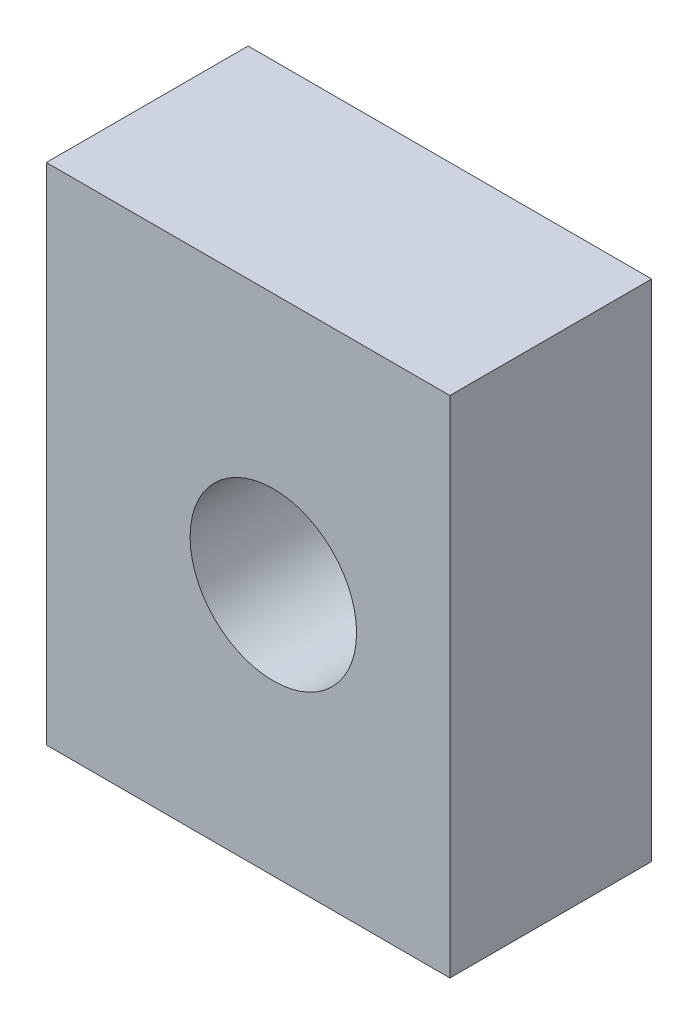
SolidWorks part; units mm, degrees
ref_plane "Front Plane" through (0, 0, 0) normal (0, 0, 1) x (1, 0, 0)
ref_plane "Top Plane" through (0, 0, 0) normal (0, 1, 0) x (1, 0, 0)
ref_plane "Right Plane" through (0, 0, 0) normal (1, 0, 0) x (0, 0, -1)
sketch "Sketch1" plane through (0, 0, 0) normal (0, 0, 1) x (1, 0, 0)
  line L0 (0, 10) -> (8, 10)
  line L1 (8, 0) -> (0, 0)
  line L2 (0, 10) -> (0, 0)
  line L3 (8, 10) -> (8, 0)
  circle A0 centre (4.5, 5) radius 1.65
  dimension "D3" = 8
  dimension "D1" = 3.3
  dimension "D2" = 4.5
  dimension "D4" = 5
  dimension "D5" = 10
extrude "Boss-Extrude1" add sketch "Sketch1" along normal blind 4
equation "\"D1@Sketch1\"= 3 + \"tol1@parametersSketch@prostheticParameters.SLDPRT\""
